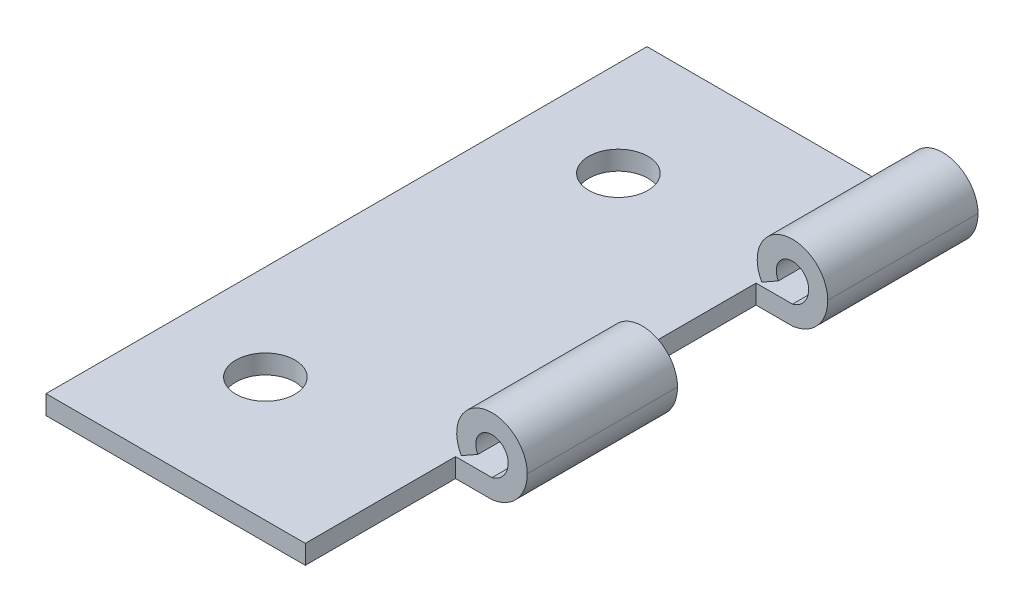
SolidWorks part; units mm, degrees
ref_plane "Front Plane" through (0, 0, 0) normal (0, 0, 1) x (1, 0, 0)
ref_plane "Top Plane" through (0, 0, 0) normal (0, 1, 0) x (1, 0, 0)
ref_plane "Right Plane" through (0, 0, 0) normal (1, 0, 0) x (0, 0, -1)
sketch "Sketch1" plane through (0, 0, 0) normal (0, 1, 0) x (1, 0, 0)
  line L0 (31, 63) -> (31, 0) construction
  line L1 (0, 0) -> (62, 0) construction
  line L2 (0, 0) -> (0, 63) construction
  line L3 (0, 63) -> (62, 63) construction
  line L4 (62, 0) -> (62, 63) construction
  circle A0 centre (10, 50) radius 3.1
  circle A2 centre (52, 50) radius 3.1
  circle A3 centre (52, 13) radius 3.1
  circle A4 centre (10, 13) radius 3.1
  dimension "D3" = 6.2
  dimension "D1" = 63
  dimension "D2" = 62
  dimension "D4" = 21
  dimension "D5" = 13
  dimension "D6" = 2
  dimension "D7" = 2
sketch "Sketch3" plane through (0, 0, 0) normal (0, 0, 1) x (1, 0, 0)
  line L0 (0, 0) -> (62, 0) construction
  line L1 (0, 0) -> (31, 0)
  line L2 (0, 0) -> (0, 2)
  line L3 (0, 2) -> (28.0278, 2)
  line L4 (31, 0) -> (31, 2) construction
  line L5 (28.0278, 2) -> (31, 2)
  line L6 (27.7788, 2.384) -> (29.521, 3.3662)
  arc A0 (32.6978, 4.2) -> (29.521, 3.3662) centre (31, 4.2) ccw
  arc A1 (34.6978, 4.2) -> (27.7788, 2.384) centre (31, 4.2) ccw
  circle A2 centre (31, 4.2) radius 3.6978 construction
  arc A3 (34.6978, 4.2) -> (31, 0) centre (30.4638, 4.2) cw
  circle A5 centre (31, 4.2) radius 1.6978 construction
  arc A6 (32.6978, 4.2) -> (31, 2) centre (30.4236, 4.2) cw
  dimension "D1" = 2
  dimension "D2" = 31
  dimension "D3" = 4.2
  dimension "D4" = 2
extrude "Boss-Extrude1" add sketch "Sketch3" against normal blind 63
ref_plane "Plane1" through (0, 12, 0) normal (0, 1, 0) x (1, 0, 0)
sketch "Sketch4" plane through (0, 12, 0) normal (0, 1, 0) x (1, 0, 0)
  line L0 (27.1812, 63) -> (37.8028, 63)
  line L4 (0, 0) -> (31, 0)
  line L5 (31, 0) -> (31, 63)
  line L6 (31, 63) -> (0, 63)
  line L7 (0, 63) -> (0, 0)
  line L8 (0, 0) -> (27.1812, 0)
  line L9 (27.1812, 0) -> (27.1812, 63)
  line L10 (27.1812, 63) -> (0, 63)
  line L11 (0, 63) -> (0, 0)
  line L15 (27.1812, 47.25) -> (37.8028, 47.25)
  line L16 (27.1812, 31.5) -> (37.8028, 31.5)
  line L17 (27.1812, 15.75) -> (37.8028, 15.75)
  line L18 (27.1812, 0) -> (37.8028, 0)
  line L19 (27.1812, 0) -> (27.1812, 63)
  line L20 (37.8028, 63) -> (37.8028, 0)
  circle A0 centre (10, 13) radius 3.1 construction
  circle A1 centre (10, 50) radius 3.1 construction
  circle A2 centre (10, 13) radius 3.1
  circle A3 centre (10, 50) radius 3.1
  dimension "D3" = 15.75
  dimension "D4" = 15.75
extrude "Cut-Extrude5" cut sketch "Sketch4" against normal blind 63 contours A3 | A2 | L20 L17 L9 L18 | L20 L15 L9 L16
sketch "Sketch5" plane through (27.1812, 0, 0) normal (1, 0, 0) x (0, 0, -1)
  line L0 (15.75, 4.2) -> (15.75, 0) construction
  line L1 (0, 7.8978) -> (15.75, 7.8978)
  line L2 (0, 7.8978) -> (0, 2.384)
  line L3 (0, 2.384) -> (15.75, 2.384)
  line L4 (15.75, 7.8978) -> (15.75, 2.384)
  line L5 (63, 2.384) -> (47.25, 2.384) construction
  line L6 (47.25, 4.2) -> (47.25, 0) construction
  line L7 (31.5, 7.8978) -> (47.25, 7.8978)
  line L8 (31.5, 7.8978) -> (31.5, 2.384)
  line L9 (31.5, 2.384) -> (47.25, 2.384)
  line L10 (47.25, 7.8978) -> (47.25, 2.384)
equation "\"D4@Sketch1\"=42/2"
equation "\"D5@Sketch1\"=(63.00mm-37mm)/2"
equation "\"D2@Sketch3\"=62/2"
equation "\"D3@Sketch4\"=63/4"
equation "\"D4@Sketch4\"=\"D3@Sketch4\""
